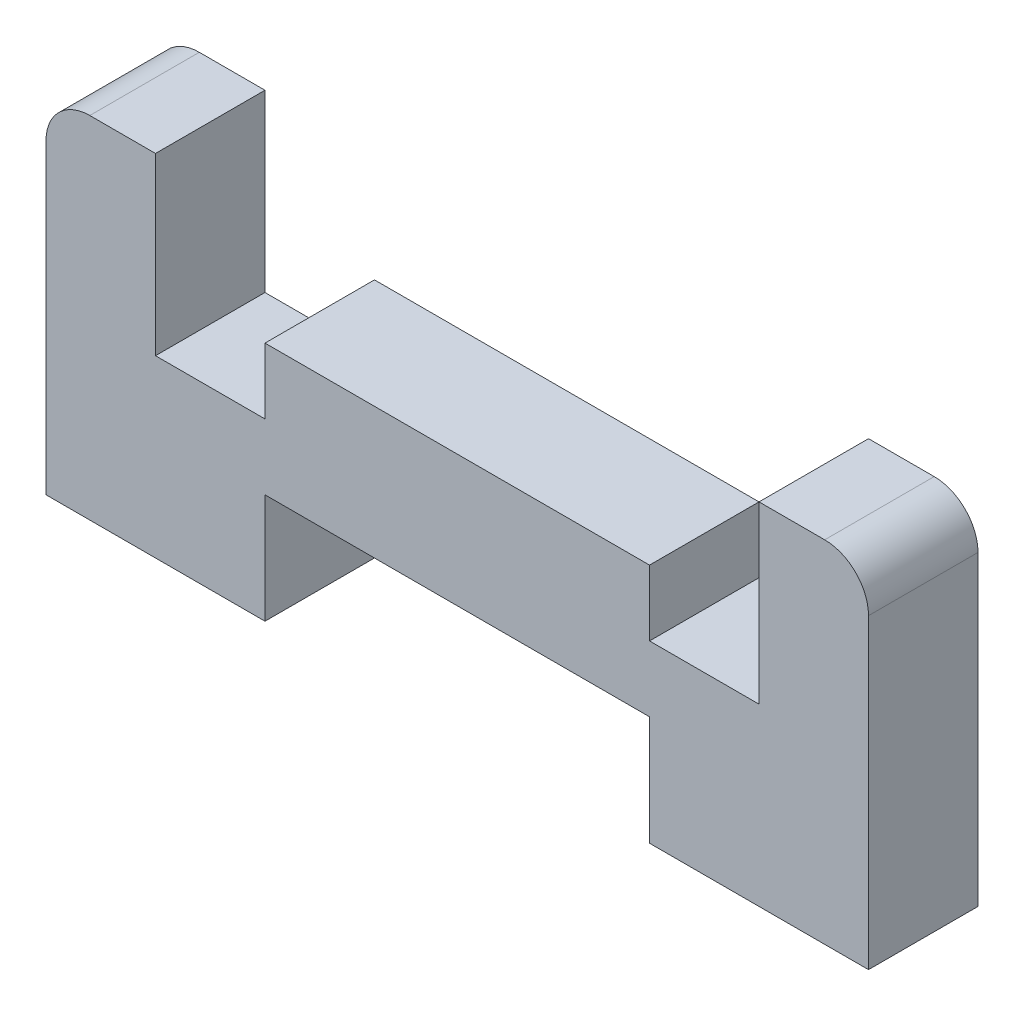
SolidWorks part; units mm, degrees
ref_plane "Front Plane" through (0, 0, 0) normal (0, 0, 1) x (1, 0, 0)
ref_plane "Top Plane" through (0, 0, 0) normal (0, 1, 0) x (1, 0, 0)
ref_plane "Right Plane" through (0, 0, 0) normal (1, 0, 0) x (0, 0, -1)
sketch "Sketch1" plane through (0, 0, 0) normal (0, 0, 1) x (1, 0, 0)
  line L0 (-11.1506, 0) -> (11.1506, 0)
  line L1 (-17.5006, 0) -> (-17.5006, 6.35)
  line L2 (-17.5006, 6.35) -> (-21.3106, 6.35)
  line L3 (-23.8506, 3.81) -> (-23.8506, -7.62)
  line L4 (-11.1506, -7.62) -> (11.1506, -7.62)
  line L5 (0, 0) -> (0, -7.62) construction
  line L6 (-23.8506, -7.62) -> (-23.8506, -13.97)
  line L7 (11.1506, -13.97) -> (23.8506, -13.97)
  line L8 (-11.1506, -13.97) -> (-11.1506, -7.62)
  line L9 (-17.5006, 0) -> (-17.5006, -3.81)
  line L10 (-17.5006, -3.81) -> (-11.1506, -3.81)
  line L11 (-11.1506, -3.81) -> (-11.1506, 0)
  line L12 (11.1506, -3.81) -> (11.1506, 0)
  line L13 (17.5006, -3.81) -> (11.1506, -3.81)
  line L14 (17.5006, 0) -> (17.5006, -3.81)
  line L15 (11.1506, -13.97) -> (11.1506, -7.62)
  line L17 (23.8506, -7.62) -> (23.8506, -13.97)
  line L18 (23.8506, 3.81) -> (23.8506, -7.62)
  line L19 (17.5006, 6.35) -> (21.3106, 6.35)
  line L20 (17.5006, 0) -> (17.5006, 6.35)
  line L21 (-23.8506, -13.97) -> (-11.1506, -13.97)
  arc A0 (-21.3106, 6.35) -> (-23.8506, 3.81) centre (-21.3106, 3.81) ccw
  arc A1 (21.3106, 6.35) -> (23.8506, 3.81) centre (21.3106, 3.81) cw
  point P15 (-23.8506, 6.35)
  point P28 (23.8506, 6.35)
  dimension "D9" = 2.54
  dimension "D1" = 17.5006
  dimension "D2" = 6.35
  dimension "D3" = 7.62
  dimension "D4" = 6.35
  dimension "D5" = 6.35
  dimension "D6" = 6.35
  dimension "D8" = 3.81
extrude "Boss-Extrude1" add sketch "Sketch1" along normal blind 6.35
